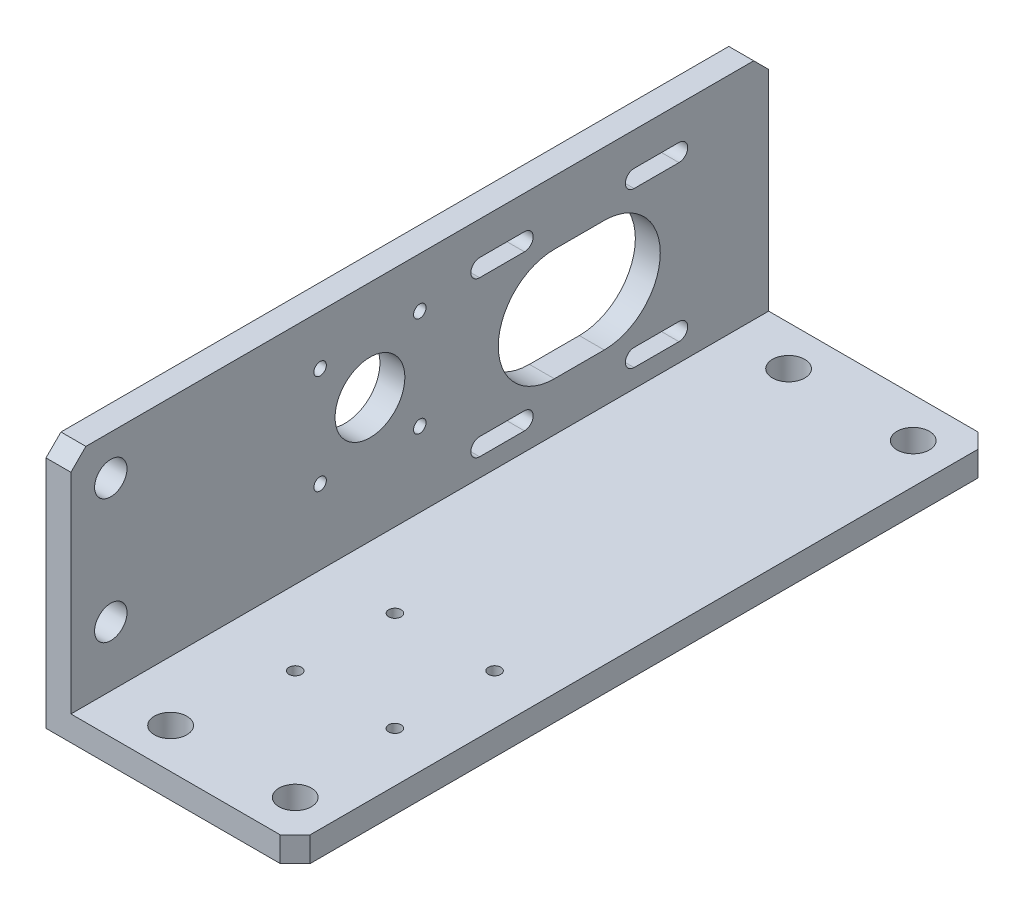
SolidWorks part; units mm, degrees
material "Lega 1060"
ref_plane "Piano frontale" through (0, 0, 0) normal (0, 0, 1) x (1, 0, 0)
ref_plane "Piano superiore" through (0, 0, 0) normal (0, 1, 0) x (1, 0, 0)
ref_plane "Piano destro" through (0, 0, 0) normal (1, 0, 0) x (0, 0, -1)
sketch "Schizzo1" plane through (0, 0, 0) normal (0, 0, 1) x (1, 0, 0)
  line L0 (0, 0) -> (0, 50)
  line L1 (0, 50) -> (5, 50)
  line L2 (5, 50) -> (5, 5)
  line L3 (5, 5) -> (50, 5)
  line L4 (50, 5) -> (50, 0)
  line L5 (50, 0) -> (0, 0)
  dimension "D1" = 5
  dimension "D2" = 5
  dimension "D3" = 50
  dimension "D4" = 50
extrude "Estrusione-Estrusione1" add sketch "Schizzo1" along normal blind 140
sketch "Schizzo2" plane through (0, 0, 0) normal (0, -1, 0) x (1, 0, 0)
  line L0 (5.4524, 132) -> (42.7933, 132) construction
  line L1 (0, 140) -> (50, 140) construction
  line L5 (50, 140) -> (50, 0) construction
  point P4 (17, 132)
  point P5 (42, 132)
  dimension "D1" = 8
  dimension "D2" = 25
  dimension "D3" = 8
sketch "Schizzo3" plane through (0, 0, 0) normal (-1, 0, 0) x (0, 0, 1)
  line L0 (132, 44.621) -> (132, 5.772) construction
  line L1 (140, 50) -> (140, 0) construction
  line L2 (140, 50) -> (0, 50) construction
  point P4 (132, 42)
  point P5 (132, 17)
  dimension "D1" = 8
  dimension "D2" = 8
  dimension "D3" = 25
hole_wizard "Foro Ø6.5 (6.5)-1" positions "Schizzo5" profile "Schizzo4" hole size "Ø6.5" standard "ISO" end condition through all
sketch "Schizzo5" plane through (0, 0, 0) normal (0, -1, 0) x (-1, 0, 0)
  point P0 (-17, -132)
  point P3 (-42, -132)
sketch "Schizzo4" plane through (17, 0, 132) normal (1, 0, 0) x (0, 0, -1)
  line L0 (0, 0) -> (0, 50)
  line L1 (0, 50) -> (3.25, 50)
  line L2 (3.25, 50) -> (3.25, 0)
  line L5 (3.25, 0) -> (0, 0)
  line L11 (0, -6.35) -> (0, 107.95) construction
  dimension "Thru Hole Dia." = 6.5
  dimension "Thru Hole Depth" = 50
hole_wizard "Foro Ø6.5 (6.5)-2" positions "Schizzo7" profile "Schizzo6" hole size "Ø6.5" standard "ISO"
sketch "Schizzo7" plane through (0, 0, 0) normal (-1, 0, 0) x (0, 0, 1)
  point P1 (132, 42)
  point P4 (132, 17)
sketch "Schizzo6" plane through (0, 42, 132) normal (0, 1, 0) x (0, 0, 1)
  line L0 (0, 0) -> (0, 6.9528)
  line L1 (0, 6.9528) -> (3.25, 5)
  line L2 (3.25, 5) -> (3.25, 0)
  line L5 (3.25, 0) -> (0, 0)
  line L10 (0, 6.9528) -> (-3.25, 5) construction
  line L11 (0, -6.35) -> (0, 107.95) construction
  dimension "Hole Dia." = 6.5
  dimension "Hole Depth" = 5
  dimension "Drill Angle" = 118
ref_plane "Piano1" through (0, 0, 70) normal (0, 0, 1) x (1, 0, 0)
mirror "Specchia1" about plane through (0, 0, 70) normal (0, 0, 1) of "Foro Ø6.5 (6.5)-1"
sketch "Schizzo10" plane through (0, 0, 0) normal (-1, 0, 0) x (0, 0, 1)
  line L3 (140, 50) -> (140, 0) construction
  line L5 (140, 50) -> (0, 50) construction
  circle A5 centre (80, 30) radius 7
  point P8 (80, 30)
  point P20 (80, 30)
  dimension "D7" = 14
  dimension "D5" = 60
  dimension "D6" = 20
extrude "Taglio-Estrusione3" cut sketch "Schizzo10" against normal up to next
sketch "Schizzo11" plane through (0, 0, 0) normal (0, -1, 0) x (1, 0, 0)
  line L0 (30, 100) -> (14.4837, 100) construction
  line L1 (30, 100) -> (4.5929, 74.5929) construction
  line L3 (50, 140) -> (50, 0) construction
  line L4 (0, 140) -> (50, 140) construction
  circle A0 centre (20, 90) radius 1.75
  circle A3 centre (20, 110) radius 1.75
  circle A4 centre (40, 110) radius 1.75
  circle A5 centre (40, 90) radius 1.75
  point P2 (30, 100)
  point P17 (30, 100)
  dimension "D2" = 3.5
  dimension "D1" = 20
  dimension "D3" = 45
  dimension "D5" = 20
  dimension "D6" = 40
  dimension "D4" = 4
sketch "Schizzo13" plane through (0, 0, 0) normal (-1, 0, 0) x (0, 0, 1)
  line L0 (68.3802, 26) -> (16.0963, 26) construction
  line L2 (140, 0) -> (0, 0) construction
  line L3 (18, 41.5563) -> (27, 41.5563) construction
  line L4 (18, 43.3063) -> (27, 43.3063)
  line L5 (18, 39.8063) -> (27, 39.8063)
  line L6 (18, 10.4437) -> (27, 10.4437) construction
  line L7 (18, 8.6937) -> (27, 8.6937)
  line L8 (18, 12.1937) -> (27, 12.1937)
  line L9 (38, 26) -> (38, 7.2619) construction
  line L10 (58, 41.5563) -> (49, 41.5563) construction
  line L11 (58, 43.3063) -> (49, 43.3063)
  line L12 (58, 39.8063) -> (49, 39.8063)
  line L13 (58, 10.4437) -> (49, 10.4437) construction
  line L14 (58, 8.6937) -> (49, 8.6937)
  line L15 (58, 12.1937) -> (49, 12.1937)
  line L16 (43, 26) -> (33, 26) construction
  line L17 (43, 14.75) -> (33, 14.75)
  line L18 (43, 37.25) -> (33, 37.25)
  arc A0 (58, 43.3063) -> (58, 39.8063) centre (58, 41.5563) cw
  circle A1 centre (80, 30) radius 7 construction
  arc A2 (18, 43.3063) -> (18, 39.8063) centre (18, 41.5563) ccw
  arc A3 (49, 39.8063) -> (49, 43.3063) centre (49, 41.5563) cw
  arc A4 (18, 8.6937) -> (18, 12.1937) centre (18, 10.4437) cw
  arc A5 (27, 12.1937) -> (27, 8.6937) centre (27, 10.4437) cw
  arc A7 (27, 39.8063) -> (27, 43.3063) centre (27, 41.5563) ccw
  arc A10 (58, 8.6937) -> (58, 12.1937) centre (58, 10.4437) ccw
  arc A11 (49, 12.1937) -> (49, 8.6937) centre (49, 10.4437) ccw
  arc A12 (43, 14.75) -> (43, 37.25) centre (43, 26) ccw
  arc A13 (33, 37.25) -> (33, 14.75) centre (33, 26) ccw
  point P8 (38, 26)
  point P13 (53.5, 41.5563)
  point P17 (22.5, 10.4437)
  point P19 (38, 26)
  point P22 (22.5, 41.5563)
  point P40 (53.5, 10.4437)
  point P47 (38, 26)
  dimension "D2" = 22.5
  dimension "D1" = 31
  dimension "D3" = 10
  dimension "D5" = 26
  dimension "D6" = 42
  dimension "D8" = 3.5
  dimension "D9" = 9
extrude "Taglio-Estrusione6" cut sketch "Schizzo13" against normal up to next
chamfer "Smusso1" distance 3 angle 45 4 edges at (50, 2.5, 0) (2.5, 50, 0) (50, 2.5, 140) (2.5, 50, 140)
sketch "Sketch1" plane through (0, 0, 0) normal (-1, 0, 0) x (0, 0, 1)
  line L0 (80, 30) -> (80, 46.7736) construction
  line L1 (80, 46.7736) -> (80, 30) construction
  line L2 (80, 30) -> (63.2264, 46.7736) construction
  line L3 (63.2264, 46.7736) -> (80, 30) construction
  line L4 (80, 30) -> (62.4784, 30) construction
  point P3 (70, 40)
  point P6 (90, 40)
  point P7 (70, 20)
  point P8 (90, 20)
  dimension "D1" = 45
  dimension "D2" = 10
hole_wizard "M3 Tapped Hole1" positions "3DSketch1" profile "Sketch2" tap size "M3" standard "ISO" end condition through all
sketch3d "3DSketch1"
  point P0 (0, 40, 70)
  point P3 (0, 40, 90)
  point P6 (0, 20, 90)
  point P9 (0, 20, 70)
sketch "Sketch2" plane through (0, 40, 70) normal (0, 1, 0) x (0, 0, 1)
  line L0 (0, 0) -> (0, 50)
  line L1 (0, 50) -> (1.25, 50)
  line L2 (1.25, 50) -> (1.25, 0)
  line L5 (1.25, 0) -> (0, 0)
  line L11 (0, -6.35) -> (0, 107.95) construction
  dimension "Thru Tap Drill Dia." = 2.5
  dimension "Thru Tap Drill Depth" = 50
cosmetic thread "Cosmetic Thread1" parameters "D2"=3
cosmetic thread "Cosmetic Thread2" parameters "D2"=3
cosmetic thread "Cosmetic Thread3" parameters "D2"=3
cosmetic thread "Cosmetic Thread4" parameters "D2"=3
hole_wizard "M3 Tapped Hole2" positions "3DSketch2" profile "Sketch3" tap size "M3" standard "ISO" end condition through all
sketch3d "3DSketch2"
  point P0 (20, 0, 110)
  point P3 (40, 0, 110)
  point P6 (40, 0, 90)
  point P9 (20, 0, 90)
sketch "Sketch3" plane through (20, 0, 110) normal (1, 0, 0) x (0, 0, -1)
  line L0 (0, 0) -> (0, 50)
  line L1 (0, 50) -> (1.25, 50)
  line L2 (1.25, 50) -> (1.25, 0)
  line L5 (1.25, 0) -> (0, 0)
  line L11 (0, -6.35) -> (0, 107.95) construction
  dimension "Thru Tap Drill Dia." = 2.5
  dimension "Thru Tap Drill Depth" = 50
cosmetic thread "Cosmetic Thread5" parameters "D2"=3
cosmetic thread "Cosmetic Thread6" parameters "D2"=3
cosmetic thread "Cosmetic Thread7" parameters "D2"=3
cosmetic thread "Cosmetic Thread8" parameters "D2"=3
